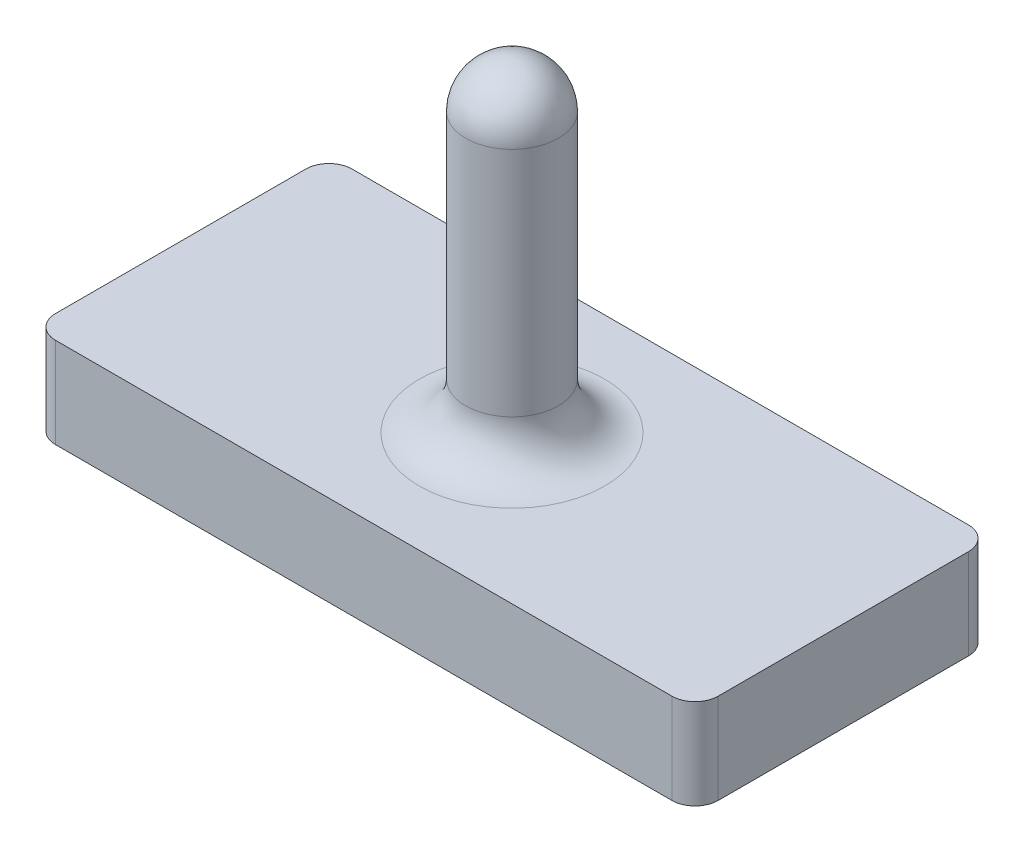
SolidWorks part; units mm, degrees
ref_plane "Front Plane" through (0, 0, 0) normal (0, 0, 1) x (1, 0, 0)
ref_plane "Top Plane" through (0, 0, 0) normal (0, 1, 0) x (1, 0, 0)
ref_plane "Right Plane" through (0, 0, 0) normal (1, 0, 0) x (0, 0, -1)
sketch "Sketch1" plane through (0, 0, 0) normal (0, 1, 0) x (1, 0, 0)
  line L1 (0, 0) -> (36.322, 0)
  line L2 (0, 0) -> (0, -16.256)
  line L3 (0, -16.256) -> (36.322, -16.256)
  line L4 (36.322, 0) -> (36.322, -16.256)
  dimension "D1" = 16.256
  dimension "D2" = 36.322
extrude "Boss-Extrude1" add sketch "Sketch1" along normal blind 4.953
sketch "Sketch2" plane through (0, 4.953, 0) normal (0, 1, 0) x (1, 0, 0)
  line L0 (0, 0) -> (0, -16.256) construction
  line L2 (0, -16.256) -> (36.322, -16.256) construction
  circle A0 centre (18.161, -8.128) radius 2.54
  dimension "D1" = 18.161
  dimension "D3" = 5.08
  dimension "D2" = 8.128
extrude "Boss-Extrude2" add sketch "Sketch2" along normal blind 17.78
fillet "Fillet1" radius 2.54 1 edges at (18.161, 22.733, 10.668)
fillet "Fillet2" radius 2.54 1 edges at (18.161, 4.953, 10.668)
fillet "Fillet3" radius 1.27 4 edges at (36.322, 2.4765, 0) (36.322, 2.4765, 16.256) (0, 2.4765, 0) (0, 2.4765, 16.256)
